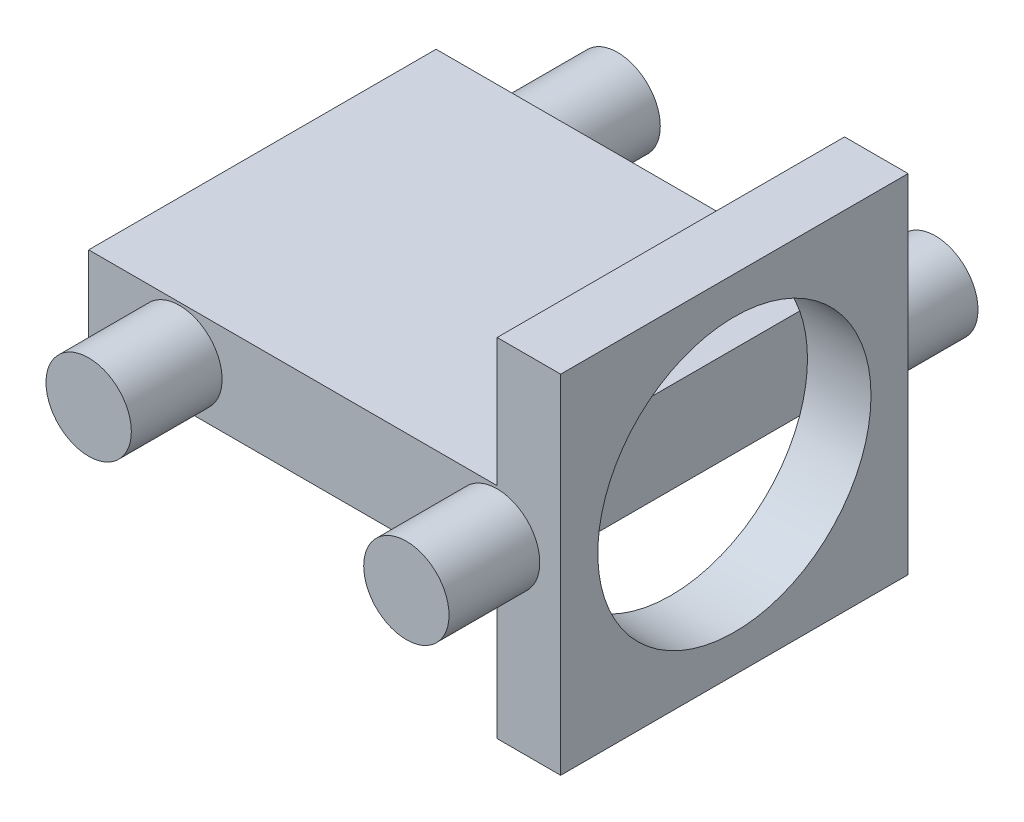
SolidWorks part; units mm, degrees
ref_plane "Front Plane" through (0, 0, 0) normal (0, 0, 1) x (1, 0, 0)
ref_plane "Top Plane" through (0, 0, 0) normal (0, 1, 0) x (1, 0, 0)
ref_plane "Right Plane" through (0, 0, 0) normal (1, 0, 0) x (0, 0, -1)
sketch "Sketch1" plane through (0, 0, 0) normal (1, 0, 0) x (0, 0, -1)
  line L1 (-19.1375, -19.1375) -> (19.1375, -19.1375)
  line L2 (-19.1375, -19.1375) -> (-19.1375, 19.1375)
  line L3 (-19.1375, 19.1375) -> (19.1375, 19.1375)
  line L4 (19.1375, -19.1375) -> (19.1375, 19.1375)
  line L5 (-19.1375, -19.1375) -> (19.1375, 19.1375) construction
  line L6 (-19.1375, 19.1375) -> (19.1375, -19.1375) construction
  circle A0 centre (0, 0) radius 15.05
  dimension "D1" = 30.1
  dimension "D2" = 38.275
  dimension "D3" = 38.275
extrude "Boss-Extrude1" add sketch "Sketch1" along normal blind 7
sketch "Sketch2" plane through (0, 0, 0) normal (-1, 0, 0) x (0, 0, 1)
  line L0 (19.1375, 19.1375) -> (19.1375, -19.1375) construction
  line L1 (-19.1375, -5) -> (19.1375, -5)
  line L2 (-19.1375, -5) -> (-19.1375, 5)
  line L3 (-19.1375, 5) -> (19.1375, 5)
  line L4 (19.1375, -5) -> (19.1375, 5)
  line L5 (-19.1375, -5) -> (19.1375, 5) construction
  line L6 (-19.1375, 5) -> (19.1375, -5) construction
  point P0 (0, 0)
  dimension "D1" = 10
extrude "Boss-Extrude2" add sketch "Sketch2" along normal blind 45
sketch "Sketch3" plane through (0, 0, 19.1375) normal (0, 0, 1) x (1, 0, 0)
  line L0 (-45, -5) -> (-45, 5) construction
  circle A0 centre (-35, 0) radius 4.7
  circle A1 centre (0, 0) radius 4.7
  dimension "D2" = 9.4
  dimension "D3" = 9.4
  dimension "D1" = 10
  dimension "D4" = 35
extrude "Boss-Extrude3" add sketch "Sketch3" along normal blind 10
mirror "Mirror1" about plane through (0, 0, 0) normal (0, 0, 1) of "Boss-Extrude3"
